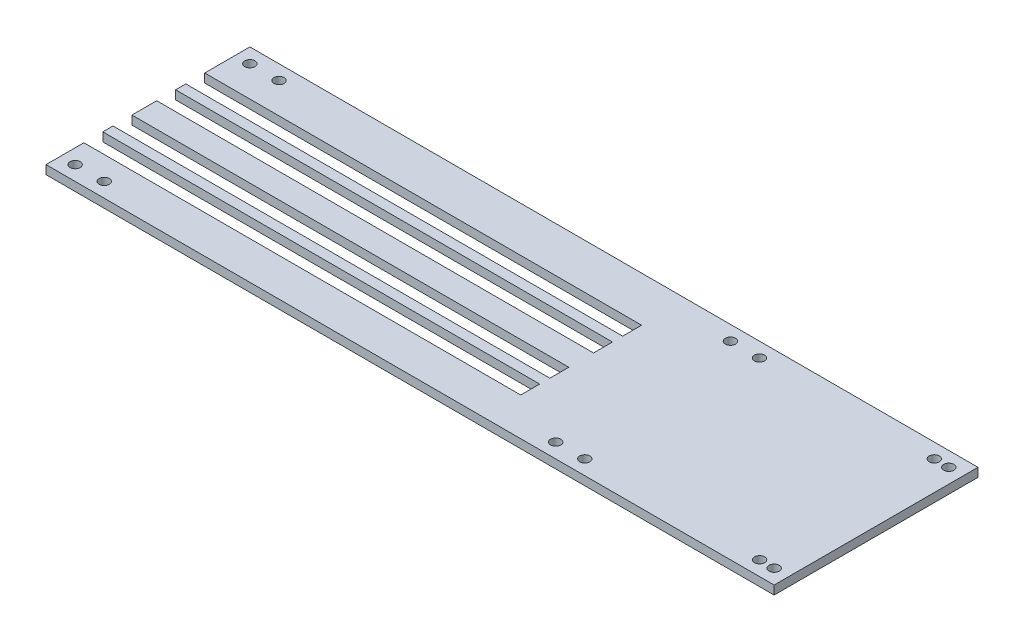
SolidWorks part; units mm, degrees
ref_plane "Front Plane" through (0, 0, 0) normal (0, 0, 1) x (1, 0, 0)
ref_plane "Top Plane" through (0, 0, 0) normal (0, 1, 0) x (1, 0, 0)
ref_plane "Right Plane" through (0, 0, 0) normal (1, 0, 0) x (0, 0, -1)
sketch "Sketch1" plane through (0, 0, 0) normal (0, 1, 0) x (1, 0, 0)
  line L0 (-150, 29.5) -> (0, 29.5)
  line L1 (0, 0) -> (100, 0)
  line L3 (-50, 70) -> (100, 70)
  line L4 (100, 0) -> (100, 70)
  line L5 (-150, 29.5) -> (-150, 38)
  line L6 (-150, 38) -> (0, 38)
  line L7 (0, 38) -> (0, 44.5)
  line L8 (0, 44.5) -> (-150, 44.5)
  line L9 (-150, 44.5) -> (-150, 48)
  line L10 (-150, 48) -> (0, 48)
  line L11 (0, 48) -> (0, 54.5)
  line L12 (0, 54.5) -> (-150, 54.5)
  line L13 (-150, 54.5) -> (-150, 70)
  line L14 (-150, 70) -> (-50, 70)
  line L16 (0, 29.5) -> (0, 23)
  line L17 (0, 23) -> (-150, 23)
  line L18 (-150, 23) -> (-150, 19.5)
  line L19 (-150, 19.5) -> (0, 19.5)
  line L20 (0, 19.5) -> (0, 13)
  line L21 (0, 13) -> (-150, 13)
  line L22 (-150, 13) -> (-150, 0)
  line L23 (-150, 0) -> (0, 0)
  dimension "D1" = 70
  dimension "D2" = 100
  dimension "D3" = 8.5
  dimension "D4" = 6.5
  dimension "D5" = 3.5
  dimension "D6" = 6.5
  dimension "D7" = 6.5
  dimension "D8" = 15.5
  dimension "D9" = 6.5
  dimension "D10" = 3.5
  dimension "D11" = 150
extrude "Boss-Extrude1" add sketch "Sketch1" along normal blind 3
ref_plane "Plane1" through (0, 0, -35) normal (0, 0, -1) x (-1, 0, 0)
sketch "Sketch2" plane through (0, 3, 0) normal (0, 1, 0) x (1, 0, 0)
  line L0 (-140, 67.7791) -> (-140, 61.3279) construction
  line L1 (-150, 70) -> (-150, 54.5) construction
  line L2 (100, 70) -> (-150, 70) construction
  line L3 (25, 70) -> (25, 63.5654) construction
  circle A0 centre (-145, 65) radius 1.75
  circle A1 centre (-135, 65) radius 1.75
  circle A2 centre (20, 65) radius 1.75
  circle A3 centre (30, 65) radius 1.75
  dimension "D1" = 3.5
  dimension "D5" = 5
  dimension "D6" = 5
  dimension "D8" = 5
  dimension "D9" = 5
  dimension "D11" = 5
  dimension "D2" = 10
  dimension "D3" = 5
  dimension "D4" = 5
  dimension "D7" = 165
  dimension "D10" = 5
extrude "Cut-Extrude1" cut sketch "Sketch2" against normal blind 10
sketch "Sketch3" plane through (0, 3, 0) normal (0, 1, 0) x (1, 0, 0)
  line L0 (100, 0) -> (100, 70) construction
  line L1 (100, 70) -> (-150, 70) construction
  circle A0 centre (95, 65) radius 1.75
  circle A1 centre (90, 65) radius 1.75
  dimension "D1" = 3.5
  dimension "D2" = 5
  dimension "D3" = 5
  dimension "D4" = 5
extrude "Cut-Extrude2" cut sketch "Sketch3" against normal blind 10
mirror "Mirror1" about plane through (0, 0, -35) normal (0, 0, -1) of "Cut-Extrude2", "Cut-Extrude1"
